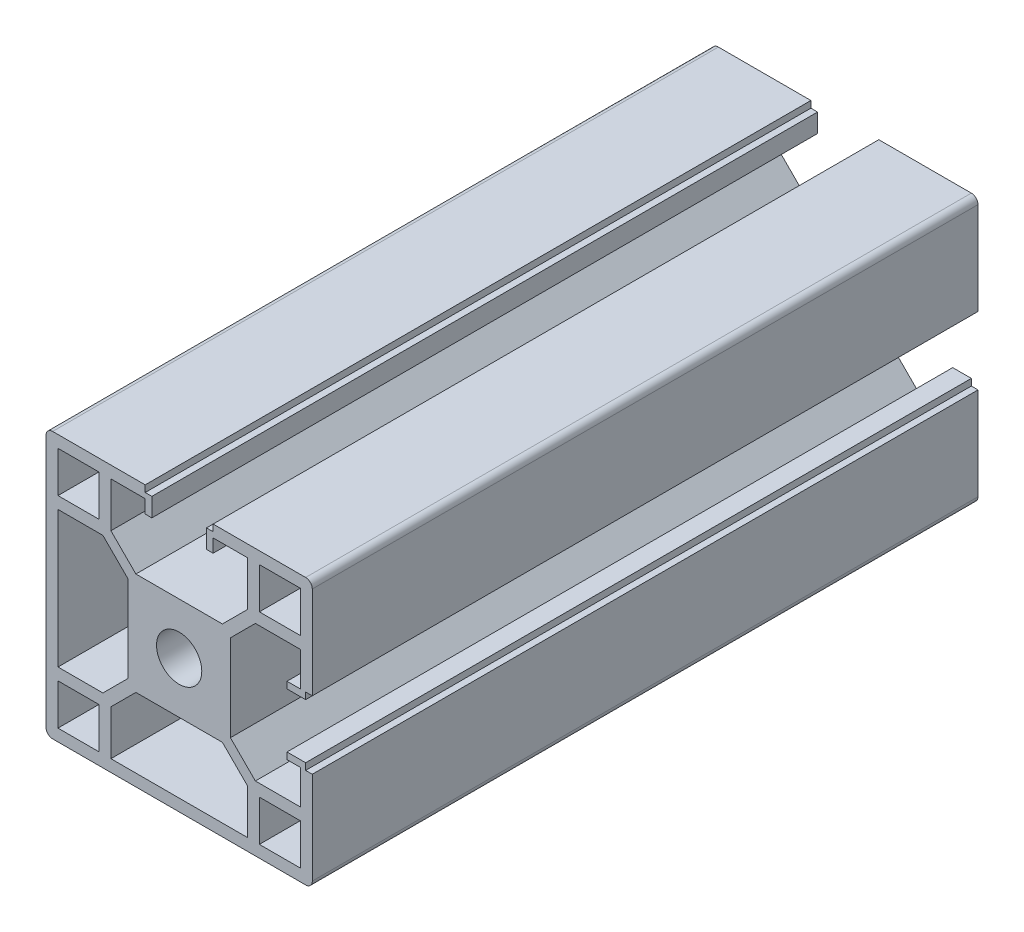
SolidWorks part; units mm, degrees
ref_plane "前视基准面" through (0, 0, 0) normal (0, 0, 1) x (1, 0, 0)
ref_plane "上视基准面" through (0, 0, 0) normal (0, 1, 0) x (1, 0, 0)
ref_plane "右视基准面" through (0, 0, 0) normal (1, 0, 0) x (0, 0, -1)
sketch "草图1" plane through (0, 0, 0) normal (0, 0, 1) x (1, 0, 0)
  line L0 (-4.0688, 19.5458) -> (-17.9688, 19.5458)
  line L1 (-18.9688, 18.5458) -> (-18.9688, 4.6458)
  line L2 (-3.0688, 15.7458) -> (-4.0688, 15.7458)
  line L3 (-4.0688, 17.7458) -> (-9.2188, 17.7458)
  line L4 (-11.0188, 17.7458) -> (-17.1688, 17.7458)
  line L5 (-17.1688, 17.7458) -> (-17.1688, 11.5958)
  line L7 (-3.0688, 18.5458) -> (-4.0688, 18.5458)
  line L8 (-6.6688, 6.0437) -> (-6.6688, -6.9521)
  line L9 (-5.4667, -8.1542) -> (7.5291, -8.1542)
  line L10 (8.7312, -6.9521) -> (8.7312, 6.0437)
  line L11 (7.5291, 7.2458) -> (-5.4667, 7.2458)
  line L12 (-17.1688, 9.7958) -> (-10.4209, 9.7958)
  line L13 (-17.1688, 11.5958) -> (-11.0188, 11.5958)
  line L14 (-9.2188, 17.7458) -> (-9.2188, 10.9979)
  line L15 (-11.0188, 17.7458) -> (-11.0188, 11.5958)
  line L16 (-4.0688, 19.5458) -> (-4.0688, 18.5458)
  line L17 (-4.0688, 17.7458) -> (-4.0688, 15.7458)
  line L18 (-3.0688, 18.5458) -> (-3.0688, 15.7458)
  line L19 (-9.2188, 10.9979) -> (-5.4667, 7.2458)
  line L20 (-10.4209, 9.7958) -> (-6.6688, 6.0437)
  line L21 (6.1312, 19.5458) -> (20.0312, 19.5458)
  line L22 (21.0312, 18.5458) -> (21.0312, 4.6458)
  line L23 (5.1312, 15.7458) -> (6.1312, 15.7458)
  line L24 (17.2312, 4.6458) -> (17.2312, 3.6458)
  line L25 (6.1312, 17.7458) -> (11.2812, 17.7458)
  line L26 (13.0812, 17.7458) -> (19.2312, 17.7458)
  line L27 (19.2312, 17.7458) -> (19.2312, 11.5958)
  line L28 (19.2312, 9.7958) -> (19.2312, 4.6458)
  line L29 (20.0312, 4.6458) -> (20.0312, 3.6458)
  line L30 (5.1312, 18.5458) -> (6.1312, 18.5458)
  line L31 (19.2312, 9.7958) -> (12.4833, 9.7958)
  line L32 (19.2312, 11.5958) -> (13.0812, 11.5958)
  line L33 (21.0312, 4.6458) -> (20.0312, 4.6458)
  line L34 (19.2312, 4.6458) -> (17.2312, 4.6458)
  line L35 (20.0312, 3.6458) -> (17.2312, 3.6458)
  line L36 (11.2812, 17.7458) -> (11.2812, 10.9979)
  line L37 (13.0812, 17.7458) -> (13.0812, 11.5958)
  line L38 (6.1312, 19.5458) -> (6.1312, 18.5458)
  line L39 (6.1312, 17.7458) -> (6.1312, 15.7458)
  line L40 (5.1312, 18.5458) -> (5.1312, 15.7458)
  line L41 (11.2812, 10.9979) -> (7.5291, 7.2458)
  line L42 (12.4833, 9.7958) -> (8.7312, 6.0437)
  line L44 (-18.9688, -19.4542) -> (-18.9688, -5.5542)
  line L46 (-11.0188, -18.6542) -> (-17.1688, -18.6542)
  line L47 (-17.1688, -18.6542) -> (-17.1688, -12.5042)
  line L48 (-17.1688, -10.7042) -> (-17.1688, 9.7958)
  line L49 (-17.1688, -10.7042) -> (-10.4209, -10.7042)
  line L50 (-17.1688, -12.5042) -> (-11.0188, -12.5042)
  line L51 (-9.2188, -18.6542) -> (-9.2188, -11.9063)
  line L52 (-11.0188, -18.6542) -> (-11.0188, -12.5042)
  line L53 (-9.2188, -11.9063) -> (-5.4667, -8.1542)
  line L54 (-10.4209, -10.7042) -> (-6.6688, -6.9521)
  line L55 (-17.9688, -20.4542) -> (20.0312, -20.4542)
  line L56 (21.0312, -19.4542) -> (21.0312, -5.5542)
  line L57 (17.2312, -5.5542) -> (17.2312, -4.5542)
  line L58 (-9.2188, -18.6542) -> (11.2812, -18.6542)
  line L59 (13.0812, -18.6542) -> (19.2312, -18.6542)
  line L60 (19.2312, -18.6542) -> (19.2312, -12.5042)
  line L61 (19.2312, -10.7042) -> (19.2312, -5.5542)
  line L62 (20.0312, -5.5542) -> (20.0312, -4.5542)
  line L63 (19.2312, -10.7042) -> (12.4833, -10.7042)
  line L64 (19.2312, -12.5042) -> (13.0812, -12.5042)
  line L65 (21.0312, -5.5542) -> (20.0312, -5.5542)
  line L66 (19.2312, -5.5542) -> (17.2312, -5.5542)
  line L67 (11.2812, -18.6542) -> (11.2812, -11.9063)
  line L68 (13.0812, -18.6542) -> (13.0812, -12.5042)
  line L69 (11.2812, -11.9063) -> (7.5291, -8.1542)
  line L70 (12.4833, -10.7042) -> (8.7312, -6.9521)
  line L71 (20.0312, -4.5542) -> (17.2312, -4.5542)
  line L72 (-18.9688, -5.5542) -> (-18.9688, 4.6458)
  arc A0 (-17.9688, 19.5458) -> (-18.9688, 18.5458) centre (-17.9688, 18.5458) ccw
  arc A1 (21.0312, 18.5458) -> (20.0312, 19.5458) centre (20.0312, 18.5458) ccw
  arc A2 (-18.9688, -19.4542) -> (-17.9688, -20.4542) centre (-17.9688, -19.4542) ccw
  arc A3 (20.0312, -20.4542) -> (21.0312, -19.4542) centre (20.0312, -19.4542) ccw
  circle A4 centre (1.0312, -0.4542) radius 3.4
extrude "凸台-拉伸1" add sketch "草图1" along normal blind 100
